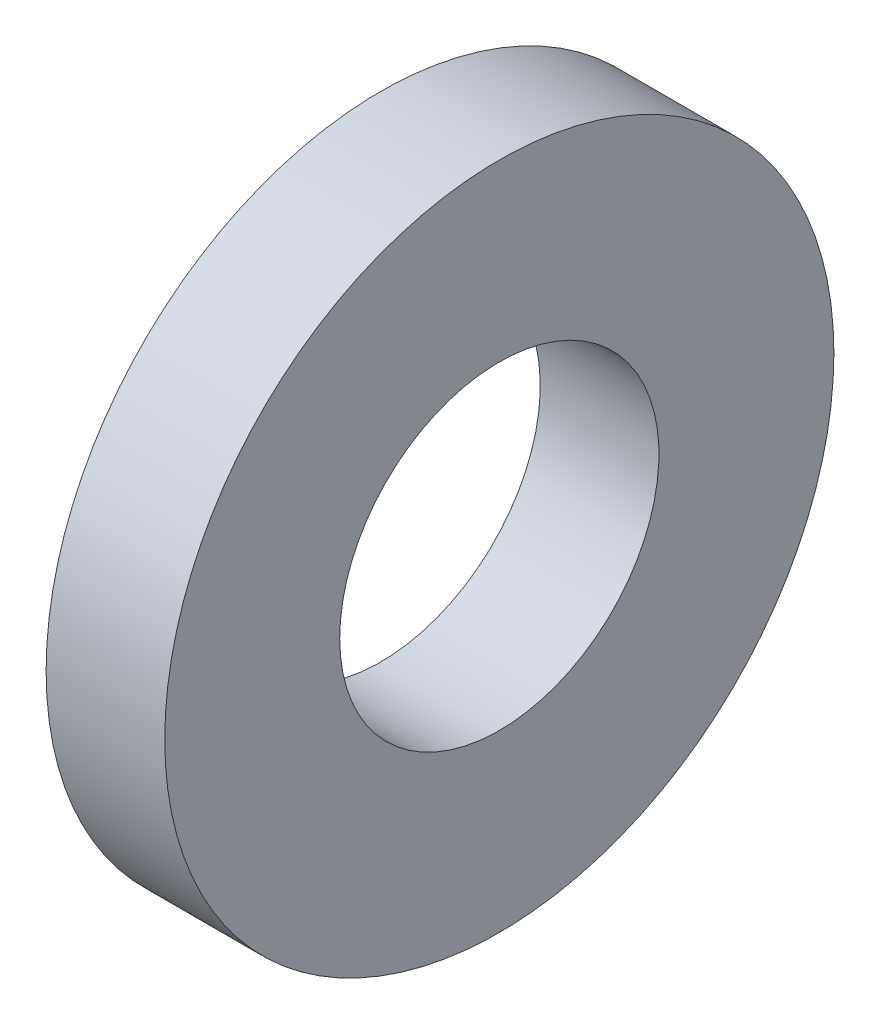
SolidWorks part; units mm, degrees
material "6061 Alloy"
ref_plane "Front Plane" through (0, 0, 0) normal (0, 0, 1) x (1, 0, 0)
ref_plane "Top Plane" through (0, 0, 0) normal (0, 1, 0) x (1, 0, 0)
ref_plane "Right Plane" through (0, 0, 0) normal (1, 0, 0) x (0, 0, -1)
sketch "Sketch1" plane through (0, 0, 0) normal (1, 0, 0) x (0, 0, -1)
  circle A0 centre (0, 0) radius 26.8605
  circle A1 centre (0, 0) radius 12.8143
  dimension "D1" = 53.721
  dimension "D2" = 25.6286
extrude "Extrude1" add sketch "Sketch1" along normal blind 9.525
